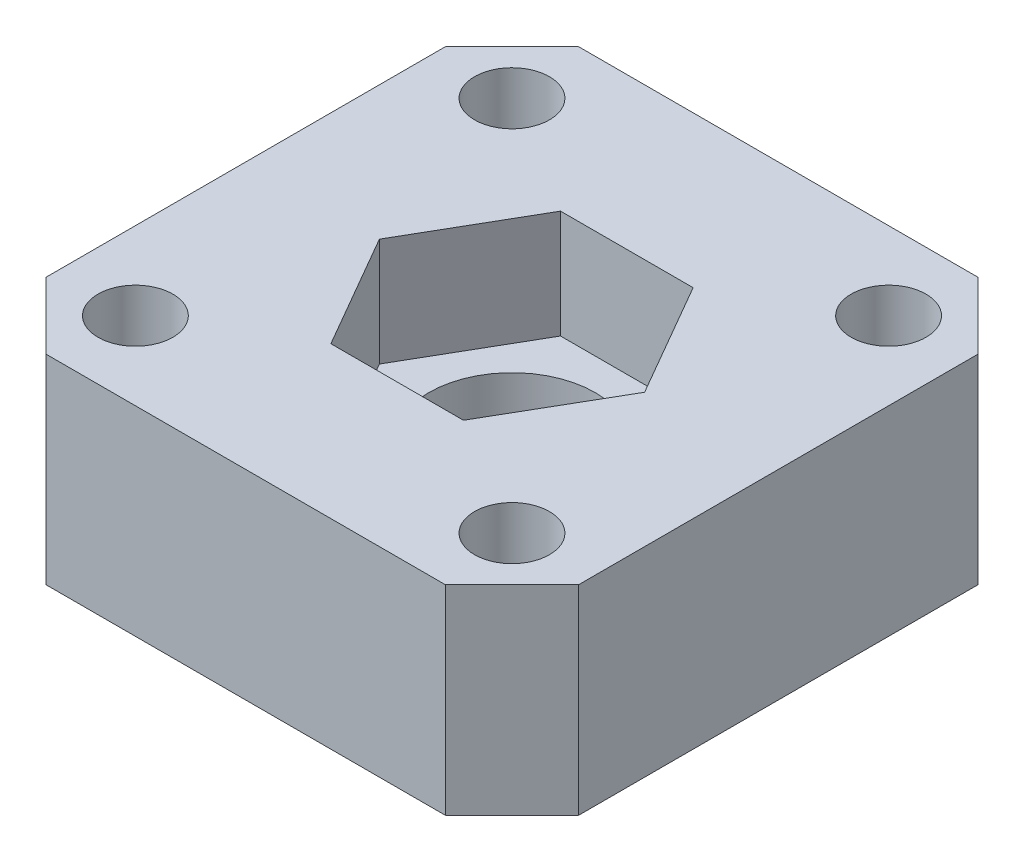
SolidWorks part; units mm, degrees
ref_plane "Front Plane" through (0, 0, 0) normal (0, 0, 1) x (1, 0, 0)
ref_plane "Top Plane" through (0, 0, 0) normal (0, 1, 0) x (1, 0, 0)
ref_plane "Right Plane" through (0, 0, 0) normal (1, 0, 0) x (0, 0, -1)
sketch "Sketch1" plane through (0, 0, 0) normal (0, 1, 0) x (1, 0, 0)
  line L1 (-16, 16) -> (16, 16)
  line L2 (-16, 16) -> (-16, -16)
  line L3 (-16, -16) -> (16, -16)
  line L4 (16, 16) -> (16, -16)
  line L5 (-16, 16) -> (16, -16) construction
  line L6 (-16, -16) -> (16, 16) construction
  circle A0 centre (0, 0) radius 5
  circle A1 centre (0, 0) radius 16 construction
  circle A2 centre (-11.3137, 11.3137) radius 2.25
  circle A3 centre (-11.3137, -11.3137) radius 2.25
  circle A4 centre (11.3137, -11.3137) radius 2.25
  circle A5 centre (11.3137, 11.3137) radius 2.25
  point P0 (0, 0)
  dimension "D3" = 10
  dimension "D4" = 32
  dimension "D5" = 4.5
  dimension "D1" = 32
  dimension "D2" = 32
extrude "Boss-Extrude1" add sketch "Sketch1" along normal blind 12
chamfer "Chamfer1" distance 4 angle 45 4 edges at (16, 6, -16) (16, 6, 16) (-16, 6, 16) (-16, 6, -16)
sketch "Sketch4" plane through (0, 12, 0) normal (0, 1, 0) x (1, 0, 0)
  line L1 (3.9837, -6.9) -> (7.9674, 0)
  line L2 (7.9674, 0) -> (3.9837, 6.9)
  line L3 (3.9837, 6.9) -> (-3.9837, 6.9)
  line L4 (-3.9837, 6.9) -> (-7.9674, 0)
  line L5 (-7.9674, 0) -> (-3.9837, -6.9)
  line L6 (-3.9837, -6.9) -> (3.9837, -6.9)
  circle A0 centre (0, 0) radius 6.9 construction
  dimension "D1" = 13.8
extrude "Cut-Extrude1" cut sketch "Sketch4" against normal blind 6.5
equation "\"dmin\"= 10"
equation "\"holesspace\"= 32"
equation "\"holes\"= 4.5"
equation "\"b\"= 12"
equation "\"nutdepth\"= 6.5"
equation "\"nut-s\"= 13.8"
equation "\"D3@Sketch1\"=\"dmin\""
equation "\"D4@Sketch1\"=\"holesspace\""
equation "\"x\"= 32"
equation "\"y\"= 32"
equation "\"D1@Sketch1\"=\"x\""
equation "\"D2@Sketch1\"=\"y\""
equation "\"D5@Sketch1\"=\"holes\""
equation "\"D1@Boss-Extrude1\"=\"b\""
equation "\"D1@Sketch4\"=\"nut-s\""
equation "\"D1@Cut-Extrude1\"=\"nutdepth\""
